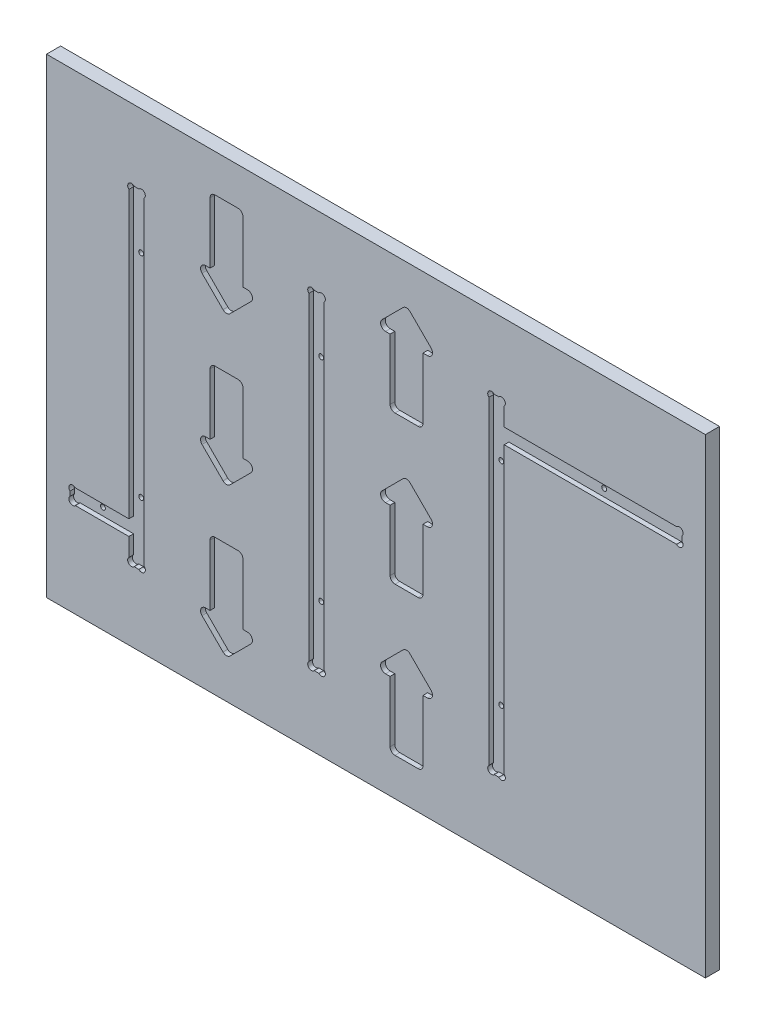
SolidWorks part; units mm, degrees
ref_plane "Plan de face" through (0, 0, 0) normal (0, 0, 1) x (1, 0, 0)
ref_plane "Plan de dessus" through (0, 0, 0) normal (0, 1, 0) x (1, 0, 0)
ref_plane "Plan de droite" through (0, 0, 0) normal (1, 0, 0) x (0, 0, -1)
sketch "Esquisse1" plane through (0, 0, 0) normal (0, 0, 1) x (1, 0, 0)
  line L1 (-60, 40) -> (220, 40)
  line L2 (-60, 40) -> (-60, -160)
  line L3 (-60, -160) -> (220, -160)
  line L4 (220, 40) -> (220, -160)
  dimension "D1" = 280
  dimension "D2" = 200
extrude "Extrusion1" add sketch "Esquisse1" along normal blind 6
sketch "Esquisse2" plane through (0, 0, 6) normal (0, 0, 1) x (1, 0, 0)
  line L0 (220, 40) -> (-60, 40) construction
  line L1 (-25, 10) -> (-18.5, 10)
  line L2 (-25, 10) -> (-25, -130)
  line L3 (-25, -130) -> (-18.5, -130)
  line L4 (-18.5, 10) -> (-18.5, -130)
  line L5 (51.5, 10) -> (58, 10)
  line L6 (51.5, 10) -> (51.5, -130)
  line L7 (51.5, -130) -> (58, -130)
  line L8 (58, 10) -> (58, -130)
  line L9 (128, 10) -> (134.5, 10)
  line L10 (128, 10) -> (128, -130)
  line L11 (128, -130) -> (134.5, -130)
  line L12 (134.5, 10) -> (134.5, -130)
  line L13 (-60, 40) -> (-60, -160) construction
  line L14 (-60, -160) -> (220, -160) construction
  dimension "D1" = 30
  dimension "D2" = 35
  dimension "D3" = 30
  dimension "D4" = 6.5
  dimension "D5" = 6.5
  dimension "D6" = 6.5
  dimension "D7" = 30
  dimension "D8" = 30
  dimension "D9" = 30
  dimension "D10" = 30
  dimension "D11" = 70
  dimension "D12" = 70
extrude "Enlèv. mat.-Extru.1" cut sketch "Esquisse2" against normal blind 2
sketch "Esquisse3" plane through (0, 0, 6) normal (0, 0, 1) x (1, 0, 0)
  line L0 (-25, 10) -> (-25, -130) construction
  line L1 (-18.5, 10) -> (-25, 10) construction
  line L2 (-18.5, -130) -> (-18.5, 10) construction
  line L3 (-25, -130) -> (-18.5, -130) construction
  circle A0 centre (-23.9, 8.9) radius 1.6
  circle A1 centre (-19.6, 8.9) radius 1.6
  circle A2 centre (-23.9, -128.9) radius 1.6
  circle A3 centre (-19.6, -128.9) radius 1.6
  circle A4 centre (52.6, 8.9) radius 1.6
  circle A5 centre (56.9, 8.9) radius 1.6
  circle A6 centre (52.6, -128.9) radius 1.6
  circle A7 centre (56.9, -128.9) radius 1.6
  circle A8 centre (129.1, 8.9) radius 1.6
  circle A9 centre (133.4, 8.9) radius 1.6
  circle A10 centre (129.1, -128.9) radius 1.6
  circle A11 centre (133.4, -128.9) radius 1.6
  dimension "D3" = 3.2
  dimension "D6" = 3.2
  dimension "D7" = 3.2
  dimension "D8" = 3.2
  dimension "D11" = 1.1
  dimension "D1" = 1.1
  dimension "D2" = 1.1
  dimension "D4" = 1.1
  dimension "D5" = 1.1
  dimension "D9" = 1.1
  dimension "D10" = 1.1
  dimension "D12" = 1.1
extrude "Enlèv. mat.-Extru.2" cut sketch "Esquisse3" against normal blind 2
sketch "Esquisse5" plane through (0, 0, 6) normal (0, 0, 1) x (1, 0, 0)
  line L0 (58, -127.7381) -> (58, 7.7381) construction
  line L1 (86, -53) -> (86, -81)
  line L2 (86, -116) -> (86, -144)
  line L3 (86, -144) -> (100, -144)
  line L4 (100, -116) -> (100, -144)
  line L5 (128, 7.7381) -> (128, -127.7381) construction
  line L6 (93, -102) -> (79, -116)
  line L7 (79, -116) -> (86, -116)
  line L8 (93, -102) -> (107, -116)
  line L9 (107, -116) -> (100, -116)
  line L10 (53.7619, -130) -> (55.7381, -130) construction
  line L11 (86, -81) -> (100, -81)
  line L12 (-60, -160) -> (220, -160) construction
  line L13 (100, -53) -> (100, -81)
  line L14 (93, -39) -> (79, -53)
  line L15 (79, -53) -> (86, -53)
  line L16 (93, -39) -> (107, -53)
  line L17 (107, -53) -> (100, -53)
  line L18 (86, 10) -> (86, -18)
  line L19 (86, -18) -> (100, -18)
  line L20 (100, 10) -> (100, -18)
  line L21 (93, 24) -> (79, 10)
  line L22 (79, 10) -> (86, 10)
  line L23 (93, 24) -> (107, 10)
  line L24 (107, 10) -> (100, 10)
  line L25 (9.5, -4) -> (2.5, -4)
  line L26 (9.5, 24) -> (23.5, 24)
  line L27 (9.5, 24) -> (9.5, -4)
  line L28 (9.5, -67) -> (2.5, -67)
  line L29 (23.5, 24) -> (23.5, -4)
  line L30 (2.5, -4) -> (16.5, -18)
  line L31 (16.5, -18) -> (30.5, -4)
  line L32 (30.5, -4) -> (23.5, -4)
  line L33 (220, 40) -> (-60, 40) construction
  line L34 (-18.5, -127.7381) -> (-18.5, 7.7381) construction
  line L35 (51.5, 7.7381) -> (51.5, -127.7381) construction
  line L36 (9.5, -39) -> (23.5, -39)
  line L37 (9.5, -39) -> (9.5, -67)
  line L38 (23.5, -39) -> (23.5, -67)
  line L39 (2.5, -67) -> (16.5, -81)
  line L40 (16.5, -81) -> (30.5, -67)
  line L41 (30.5, -67) -> (23.5, -67)
  line L42 (9.5, -130) -> (2.5, -130)
  line L43 (9.5, -102) -> (23.5, -102)
  line L44 (9.5, -102) -> (9.5, -130)
  line L45 (23.5, -102) -> (23.5, -130)
  line L46 (2.5, -130) -> (16.5, -144)
  line L47 (16.5, -144) -> (30.5, -130)
  line L48 (30.5, -130) -> (23.5, -130)
  dimension "D10" = 16
  dimension "D13" = 28
  dimension "D1" = 28
  dimension "D2" = 28
  dimension "D3" = 14
  dimension "D4" = 7
  dimension "D5" = 7
  dimension "D6" = 7
  dimension "D7" = 14
  dimension "D8" = 14
  dimension "D9" = 28
  dimension "D11" = 28
  dimension "D12" = 28
  dimension "D14" = 16
  dimension "D15" = 7
  dimension "D16" = 7
  dimension "D17" = 14
  dimension "D18" = 7
  dimension "D19" = 14
extrude "Enlèv. mat.-Extru.4" cut sketch "Esquisse5" against normal blind 2
fillet "Congé1" radius 2.1 30 edges at (107, -116, 5) (93, -102, 5) (79, -116, 5) (100, -144, 5) (86, -144, 5) (79, 10, 5) (107, 10, 5) (93, 24, 5) (100, -18, 5) (86, -18, 5) (100, -81, 5) (86, -81, 5) (107, -53, 5) (79, -53, 5) (93, -39, 5) (16.5, -144, 5) (2.5, -130, 5) (30.5, -130, 5) (23.5, -102, 5) (9.5, -102, 5) (9.5, -39, 5) (2.5, -67, 5) (16.5, -81, 5) (30.5, -67, 5) (23.5, -39, 5) (23.5, 24, 5) (30.5, -4, 5) (2.5, -4, 5) (9.5, 24, 5) (16.5, -18, 5)
sketch "Esquisse6" plane through (0, 0, 6) normal (0, 0, 1) x (1, 0, 0)
  line L0 (-25, 7.7381) -> (-25, -127.7381) construction
  line L1 (-25, -113.5) -> (-50, -113.5)
  line L2 (-25, -113.5) -> (-25, -120)
  line L3 (-25, -120) -> (-50, -120)
  line L4 (-50, -113.5) -> (-50, -120)
  line L5 (-22.7381, -130) -> (-20.7619, -130) construction
  line L6 (134.5, -127.7381) -> (134.5, 7.7381) construction
  line L7 (134.5, 0) -> (210, 0)
  line L8 (134.5, 0) -> (134.5, -6.5)
  line L9 (134.5, -6.5) -> (210, -6.5)
  line L10 (210, 0) -> (210, -6.5)
  line L11 (132.2381, 10) -> (130.2619, 10) construction
  line L12 (220, -160) -> (220, 40) construction
  dimension "D1" = 6.5
  dimension "D2" = 10
  dimension "D3" = 25
  dimension "D4" = 6.5
  dimension "D5" = 10
  dimension "D6" = 10
  dimension "D7" = 75.5
extrude "Enlèv. mat.-Extru.5" cut sketch "Esquisse6" against normal blind 2
sketch "Esquisse7" plane through (0, 0, 6) normal (0, 0, 1) x (1, 0, 0)
  line L0 (210, 0) -> (134.5, 0) construction
  line L1 (210, -6.5) -> (210, 0) construction
  line L2 (134.5, -6.5) -> (210, -6.5) construction
  line L3 (-50, -113.5) -> (-50, -120) construction
  line L4 (-25, -113.5) -> (-50, -113.5) construction
  line L5 (-50, -120) -> (-25, -120) construction
  circle A0 centre (208.9, -1.1) radius 1.6
  circle A1 centre (208.9, -5.4) radius 1.6
  circle A2 centre (-48.9, -114.6) radius 1.6
  circle A3 centre (-48.9, -118.9) radius 1.6
  point P10 (210, -3.25)
  dimension "D1" = 1.1
  dimension "D3" = 1.1
  dimension "D5" = 1.1
  dimension "D2" = 1.1
  dimension "D4" = 1.1
  dimension "D6" = 1.1
  dimension "D7" = 1.1
  dimension "D8" = 1.1
extrude "Enlèv. mat.-Extru.6" cut sketch "Esquisse7" against normal blind 2
sketch "Esquisse4" plane through (0, 0, 6) normal (0, 0, 1) x (1, 0, 0)
  line L0 (-18.5, -127.7381) -> (-18.5, 7.7381) construction
  line L1 (-20.7619, 10) -> (-22.7381, 10) construction
  line L2 (-22.7381, -130) -> (-20.7619, -130) construction
  line L3 (-25, -113.5) -> (-47.7381, -113.5) construction
  line L4 (-50, -115.7619) -> (-50, -117.7381) construction
  line L5 (134.5, -6.5) -> (207.7381, -6.5) construction
  line L6 (210, -4.2381) -> (210, -2.2619) construction
  circle A0 centre (-21.75, -15) radius 1.05
  circle A1 centre (-21.75, -105) radius 1.05
  circle A2 centre (54.75, -15) radius 1.05
  circle A3 centre (54.75, -105) radius 1.05
  circle A4 centre (131.25, -15) radius 1.05
  circle A5 centre (131.25, -105) radius 1.05
  circle A6 centre (-38, -116.75) radius 1.05
  circle A7 centre (175, -3.25) radius 1.05
  dimension "D1" = 2.1
  dimension "D2" = 2.1
  dimension "D4" = 3.25
  dimension "D5" = 25
  dimension "D7" = 2.1
  dimension "D10" = 2.1
  dimension "D11" = 3.25
  dimension "D3" = 3.25
  dimension "D6" = 25
  dimension "D8" = 3.25
  dimension "D9" = 12
  dimension "D12" = 35
extrude "Enlèv. mat.-Extru.3" cut sketch "Esquisse4" against normal through all
